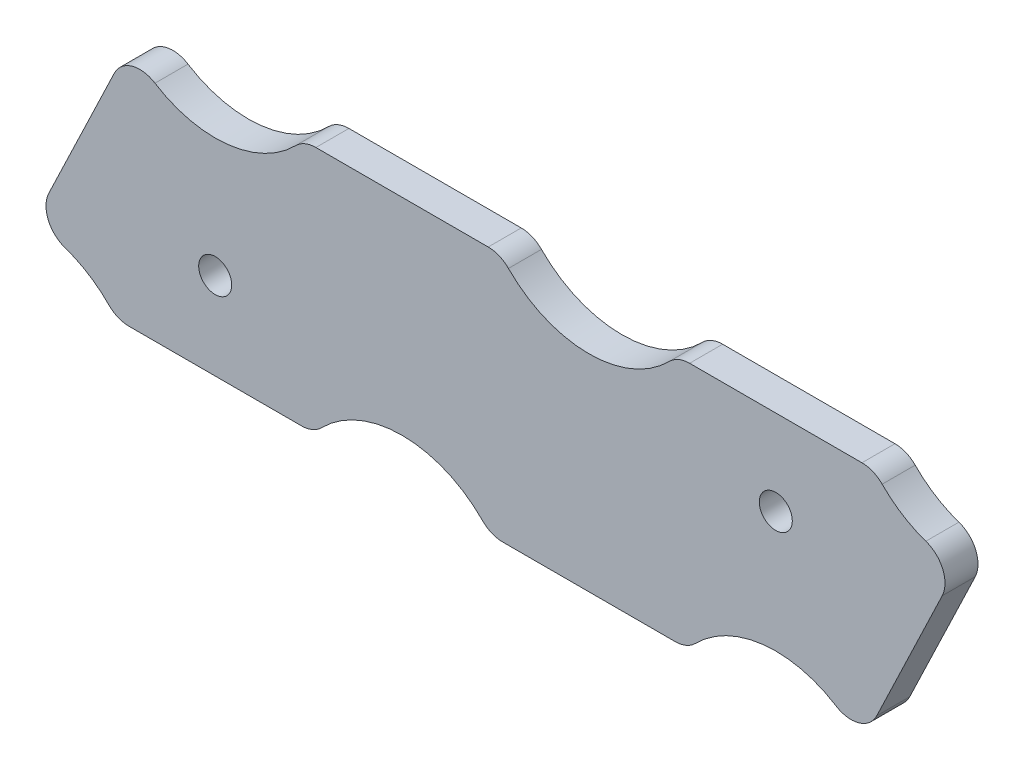
SolidWorks part; units mm, degrees
material "3003-H14"
ref_plane "X-Y Datum" through (0, 0, 0) normal (0, 0, 1) x (1, 0, 0)
ref_plane "X-Z Datum" through (0, 0, 0) normal (0, 1, 0) x (1, 0, 0)
ref_plane "Y-Z Datum" through (0, 0, 0) normal (1, 0, 0) x (0, 0, -1)
sketch "Sketch3" plane through (0, 0, 0) normal (0, 0, 1) x (1, 0, 0)
  line L0 (10.775, 10.775) -> (22.275, 34.775) construction
  line L1 (0, 0) -> (156.4633, 0) construction
  line L2 (0, 0) -> (0, 56.3098) construction
  line L3 (0, 56.3098) -> (156.4633, 56.3098) construction
  line L4 (156.4633, 0) -> (156.4633, 56.3098) construction
  line L5 (33.775, 10.775) -> (45.275, 34.775) construction
  line L6 (56.775, 10.775) -> (68.275, 34.775) construction
  line L7 (16.525, 22.775) -> (62.525, 22.775) construction
  line L8 (33.775, 10.775) -> (22.275, 34.775) construction
  line L9 (45.275, 34.775) -> (56.775, 10.775) construction
  line L10 (10.775, 10.775) -> (33.775, 10.775) construction
  line L11 (56.775, 10.775) -> (33.775, 10.775) construction
  line L12 (22.275, 34.775) -> (45.275, 34.775) construction
  line L13 (68.275, 34.775) -> (45.275, 34.775) construction
  line L14 (22.275, 34.775) -> (22.275, 10.775) construction
  line L15 (45.275, 10.775) -> (45.275, 34.775) construction
  line L16 (33.775, 10.775) -> (33.775, 34.775) construction
  line L17 (56.775, 34.775) -> (56.775, 10.775) construction
  line L18 (13.4804, 9.4786) -> (24.9804, 33.4786)
  line L19 (36.4804, 9.4786) -> (47.9804, 33.4786)
  line L20 (59.4804, 9.4786) -> (70.9804, 33.4786)
  line L21 (8.0696, 12.0714) -> (19.5696, 36.0714)
  line L22 (31.0696, 12.0714) -> (42.5696, 36.0714)
  line L23 (54.0696, 12.0714) -> (65.5696, 36.0714)
  line L24 (17.8152, 18.525) -> (57.1619, 18.525)
  line L25 (21.8881, 27.025) -> (61.2348, 27.025)
  line L26 (16.525, 27.025) -> (62.525, 27.025) construction
  line L27 (16.525, 18.525) -> (62.525, 18.525) construction
  line L28 (16.0692, 14.8813) -> (28.4808, 14.8813)
  line L29 (39.9808, 30.6687) -> (27.5692, 30.6687)
  line L48 (56.775, 10.775) -> (68.275, 10.775) construction
  line L49 (68.275, 10.775) -> (68.275, 34.775) construction
  line L50 (62.9808, 30.6687) -> (50.5692, 30.6687)
  line L51 (39.0692, 14.8813) -> (51.4808, 14.8813)
  circle A0 centre (10.775, 10.775) radius 10.775 construction
  circle A1 centre (33.775, 10.775) radius 10.775 construction
  circle A2 centre (22.275, 34.775) radius 10.775 construction
  circle A3 centre (45.275, 34.775) radius 10.775 construction
  circle A4 centre (68.275, 34.775) radius 10.775 construction
  circle A5 centre (56.775, 10.775) radius 10.775 construction
  circle A6 centre (10.775, 10.775) radius 4.7 construction
  circle A7 centre (33.775, 10.775) radius 4.7 construction
  circle A8 centre (56.775, 10.775) radius 4.7 construction
  circle A9 centre (68.275, 34.775) radius 4.7 construction
  circle A10 centre (45.275, 34.775) radius 4.7 construction
  circle A11 centre (22.275, 34.775) radius 4.7 construction
  circle A12 centre (22.275, 34.775) radius 6.7
  circle A13 centre (10.775, 10.775) radius 6.7
  circle A14 centre (33.775, 10.775) radius 6.7
  circle A15 centre (45.275, 34.775) radius 6.7
  circle A16 centre (68.275, 34.775) radius 6.7
  circle A17 centre (56.775, 10.775) radius 6.7
  circle A18 centre (125.775, 10.775) radius 10.775 construction
  circle A19 centre (102.775, 10.775) radius 10.775 construction
  circle A20 centre (79.775, 10.775) radius 10.775 construction
  circle A21 centre (91.275, 34.775) radius 10.775 construction
  circle A22 centre (114.275, 34.775) radius 10.775 construction
  circle A23 centre (137.275, 34.775) radius 10.775 construction
  dimension "D1" = 21.55
  dimension "D9" = 9.4
  dimension "D2" = 23
  dimension "D3" = 24
  dimension "D4" = 11.5
  dimension "D6" = 23
  dimension "D8" = 23
  dimension "D10" = 3
  dimension "D11" = 3
  dimension "D12" = 4.25
  dimension "D13" = 4.25
  dimension "D14" = 2
  dimension "D5" = 6
  dimension "D7" = 5
extrude "Boss-Extrude1" add sketch "Sketch3" along normal blind 2.032
ref_plane "Plane1" through (68.275, 0, 0) normal (1, 0, 0) x (0, 0, -1)
fillet "Fillet1" radius 2 12 edges at (62.9808, 30.6687, 1.016) (50.5692, 30.6687, 1.016) (39.9808, 30.6687, 1.016) (27.5692, 30.6687, 1.016) (16.0692, 14.8813, 1.016) (28.4808, 14.8813, 1.016) (39.0692, 14.8813, 1.016) (51.4808, 14.8813, 1.016) (68.3917, 28.076, 1.016) (62.0692, 14.8813, 1.016) (10.6583, 17.474, 1.016) (16.9808, 30.6687, 1.016)
sketch "Sketch4" plane through (0, 0, 2.032) normal (0, 0, 1) x (1, 0, 0)
  circle A0 centre (22.275, 20.4921) radius 1.016
  circle A1 centre (56.775, 25.1696) radius 1.016
  point P0 (56.775, 25.1696)
  point P1 (22.275, 20.4921)
  dimension "D1" = 2.032
extrude "Cut-Extrude1" cut sketch "Sketch4" against normal through all
sketch "Sketch5" [suppressed] plane through (0, 0, 2.032) normal (0, 0, 1) x (1, 0, 0)
  line L0 (13.8196, 24.0714) -> (66.4728, 24.0714)
  line L1 (11.8041, 19.8652) -> (15.835, 28.2776) construction
  line L2 (63.215, 17.2724) -> (67.2459, 25.6848) construction
  line L3 (65.2304, 21.4786) -> (12.5772, 21.4786)
  line L5 (40.1462, 24.0714) -> (40.1462, 21.4786)
  line L6 (38.9038, 21.4786) -> (38.9038, 24.0714)
  line L7 (38.9038, 22.775) -> (40.1462, 22.775)
  line L9 (16.025, 27.275) -> (63.025, 27.275)
  line L10 (16.025, 27.275) -> (16.025, 18.275)
  line L11 (16.025, 18.275) -> (63.025, 18.275)
  line L12 (63.025, 27.275) -> (63.025, 18.275)
  line L13 (16.025, 27.275) -> (63.025, 18.275) construction
  line L14 (16.025, 18.275) -> (63.025, 27.275) construction
  point P11 (40.1462, 24.0714)
  point P15 (39.525, 22.775)
  dimension "D1" = 47
  dimension "D2" = 9
sketch "Sketch6" plane through (0, 0, 2.032) normal (0, 0, 1) x (1, 0, 0)
  line L0 (16.0641, 28.1678) -> (12.0331, 19.7554)
  line L1 (16.9721, 15.1353) -> (27.5779, 15.1353)
  line L2 (39.9721, 15.1353) -> (50.5779, 15.1353)
  line L3 (62.9859, 17.3822) -> (67.0169, 25.7946)
  line L4 (62.0779, 30.4147) -> (51.4721, 30.4147)
  line L5 (39.0779, 30.4147) -> (28.4721, 30.4147)
  line L6 (62.0779, 30.6687) -> (51.4721, 30.6687)
  line L7 (39.0779, 30.6687) -> (28.4721, 30.6687)
  line L8 (15.835, 28.2776) -> (11.8041, 19.8652)
  line L9 (16.9721, 14.8813) -> (27.5779, 14.8813)
  line L10 (39.9721, 14.8813) -> (50.5779, 14.8813)
  line L11 (63.215, 17.2724) -> (67.2459, 25.6848)
  line L12 (62.0779, 30.6687) -> (51.4721, 30.6687)
  line L13 (39.0779, 30.6687) -> (28.4721, 30.6687)
  line L14 (15.835, 28.2776) -> (11.8041, 19.8652)
  line L15 (16.9721, 14.8813) -> (27.5779, 14.8813)
  line L16 (39.9721, 14.8813) -> (50.5779, 14.8813)
  line L17 (63.215, 17.2724) -> (67.2459, 25.6848)
  arc A0 (12.0331, 19.7554) -> (13.0392, 17.3501) centre (13.6077, 19.0009) ccw
  arc A1 (15.7284, 15.6558) -> (13.0392, 17.3501) centre (10.775, 10.775) ccw
  arc A2 (15.7284, 15.6558) -> (16.9721, 15.1353) centre (16.9721, 16.8813) ccw
  arc A3 (27.5779, 15.1353) -> (28.8216, 15.6558) centre (27.5779, 16.8813) ccw
  arc A4 (38.7284, 15.6558) -> (28.8216, 15.6558) centre (33.775, 10.775) ccw
  arc A5 (38.7284, 15.6558) -> (39.9721, 15.1353) centre (39.9721, 16.8813) ccw
  arc A6 (50.5779, 15.1353) -> (51.8216, 15.6558) centre (50.5779, 16.8813) ccw
  arc A7 (60.4809, 16.6593) -> (51.8216, 15.6558) centre (56.775, 10.775) ccw
  arc A8 (60.4809, 16.6593) -> (62.9859, 17.3822) centre (61.4113, 18.1367) ccw
  arc A9 (67.0169, 25.7946) -> (66.0108, 28.1999) centre (65.4423, 26.5491) ccw
  arc A10 (63.3216, 29.8942) -> (66.0108, 28.1999) centre (68.275, 34.775) ccw
  arc A11 (63.3216, 29.8942) -> (62.0779, 30.4147) centre (62.0779, 28.6687) ccw
  arc A12 (51.4721, 30.4147) -> (50.2284, 29.8942) centre (51.4721, 28.6687) ccw
  arc A13 (40.3216, 29.8942) -> (50.2284, 29.8942) centre (45.275, 34.775) ccw
  arc A14 (40.3216, 29.8942) -> (39.0779, 30.4147) centre (39.0779, 28.6687) ccw
  arc A15 (28.4721, 30.4147) -> (27.2284, 29.8942) centre (28.4721, 28.6687) ccw
  arc A16 (18.5691, 28.8907) -> (27.2284, 29.8942) centre (22.275, 34.775) ccw
  arc A17 (18.5691, 28.8907) -> (16.0641, 28.1678) centre (17.6387, 27.4133) ccw
  arc A18 (63.5026, 30.0725) -> (66.0935, 28.4401) centre (68.275, 34.775) ccw
  arc A19 (63.5026, 30.0725) -> (62.0779, 30.6687) centre (62.0779, 28.6687) ccw
  arc A20 (51.4721, 30.6687) -> (50.0474, 30.0725) centre (51.4721, 28.6687) ccw
  arc A21 (40.5026, 30.0725) -> (50.0474, 30.0725) centre (45.275, 34.775) ccw
  arc A22 (40.5026, 30.0725) -> (39.0779, 30.6687) centre (39.0779, 28.6687) ccw
  arc A23 (28.4721, 30.6687) -> (27.0474, 30.0725) centre (28.4721, 28.6687) ccw
  arc A24 (18.7045, 29.1057) -> (27.0474, 30.0725) centre (22.275, 34.775) ccw
  arc A25 (18.7045, 29.1057) -> (15.835, 28.2776) centre (17.6387, 27.4133) ccw
  arc A26 (11.8041, 19.8652) -> (12.9565, 17.1099) centre (13.6077, 19.0009) ccw
  arc A27 (15.5474, 15.4775) -> (12.9565, 17.1099) centre (10.775, 10.775) ccw
  arc A28 (15.5474, 15.4775) -> (16.9721, 14.8813) centre (16.9721, 16.8813) ccw
  arc A29 (27.5779, 14.8813) -> (29.0026, 15.4775) centre (27.5779, 16.8813) ccw
  arc A30 (38.5474, 15.4775) -> (29.0026, 15.4775) centre (33.775, 10.775) ccw
  arc A31 (38.5474, 15.4775) -> (39.9721, 14.8813) centre (39.9721, 16.8813) ccw
  arc A32 (50.5779, 14.8813) -> (52.0026, 15.4775) centre (50.5779, 16.8813) ccw
  arc A33 (60.3455, 16.4443) -> (52.0026, 15.4775) centre (56.775, 10.775) ccw
  arc A34 (60.3455, 16.4443) -> (63.215, 17.2724) centre (61.4113, 18.1367) ccw
  arc A35 (67.2459, 25.6848) -> (66.0935, 28.4401) centre (65.4423, 26.5491) ccw
  arc A36 (63.5026, 30.0725) -> (66.0935, 28.4401) centre (68.275, 34.775) ccw
  arc A37 (63.5026, 30.0725) -> (62.0779, 30.6687) centre (62.0779, 28.6687) ccw
  arc A38 (51.4721, 30.6687) -> (50.0474, 30.0725) centre (51.4721, 28.6687) ccw
  arc A39 (40.5026, 30.0725) -> (50.0474, 30.0725) centre (45.275, 34.775) ccw
  arc A40 (40.5026, 30.0725) -> (39.0779, 30.6687) centre (39.0779, 28.6687) ccw
  arc A41 (28.4721, 30.6687) -> (27.0474, 30.0725) centre (28.4721, 28.6687) ccw
  arc A42 (18.7045, 29.1057) -> (27.0474, 30.0725) centre (22.275, 34.775) ccw
  arc A43 (18.7045, 29.1057) -> (15.835, 28.2776) centre (17.6387, 27.4133) ccw
  arc A44 (11.8041, 19.8652) -> (12.9565, 17.1099) centre (13.6077, 19.0009) ccw
  arc A45 (15.5474, 15.4775) -> (12.9565, 17.1099) centre (10.775, 10.775) ccw
  arc A46 (15.5474, 15.4775) -> (16.9721, 14.8813) centre (16.9721, 16.8813) ccw
  arc A47 (27.5779, 14.8813) -> (29.0026, 15.4775) centre (27.5779, 16.8813) ccw
  arc A48 (38.5474, 15.4775) -> (29.0026, 15.4775) centre (33.775, 10.775) ccw
  arc A49 (38.5474, 15.4775) -> (39.9721, 14.8813) centre (39.9721, 16.8813) ccw
  arc A50 (50.5779, 14.8813) -> (52.0026, 15.4775) centre (50.5779, 16.8813) ccw
  arc A51 (60.3455, 16.4443) -> (52.0026, 15.4775) centre (56.775, 10.775) ccw
  arc A52 (60.3455, 16.4443) -> (63.215, 17.2724) centre (61.4113, 18.1367) ccw
  arc A53 (67.2459, 25.6848) -> (66.0935, 28.4401) centre (65.4423, 26.5491) ccw
  dimension "D1" = 0
  dimension "D2" = 0.254
extrude "Cut-Extrude2" cut sketch "Sketch6" against normal through all
